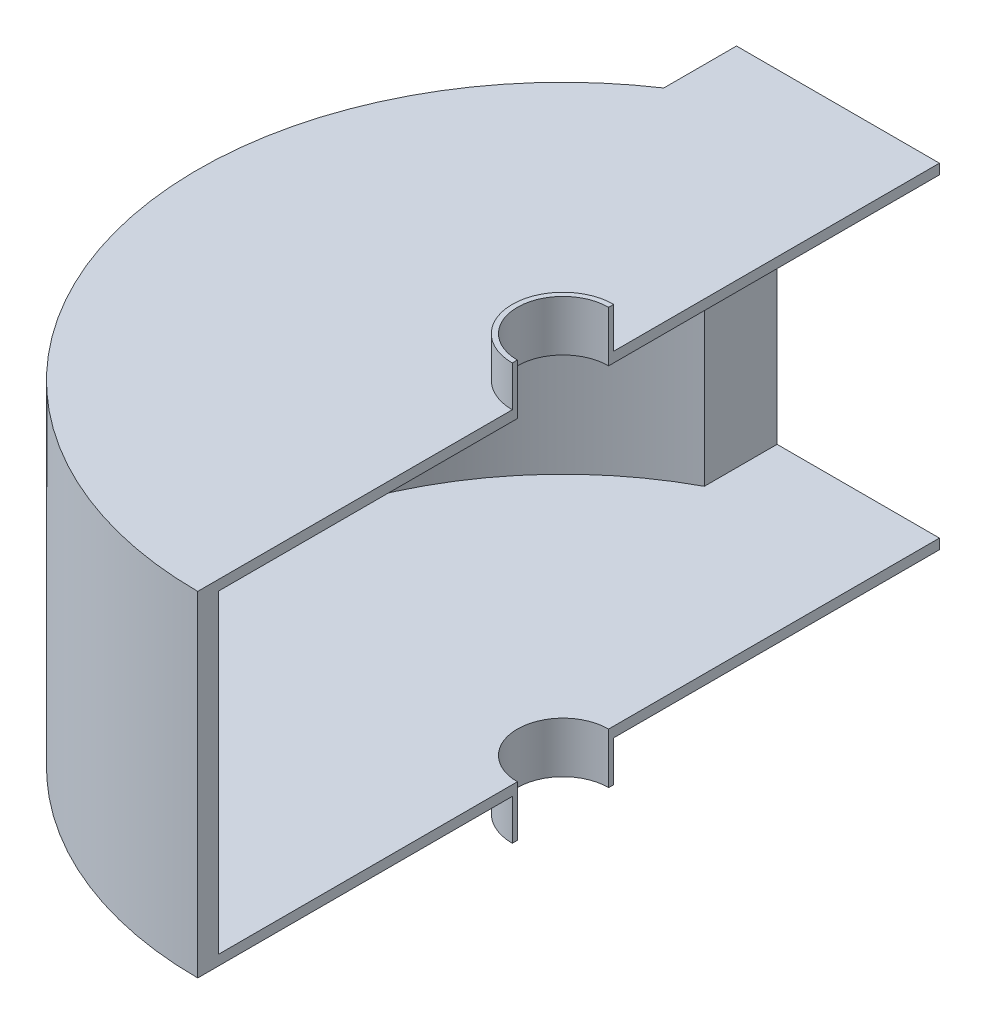
SolidWorks part; units mm, degrees
ref_plane "Front Plane" through (0, 0, 0) normal (0, 0, 1) x (1, 0, 0)
ref_plane "Top Plane" through (0, 0, 0) normal (0, 1, 0) x (1, 0, 0)
ref_plane "Right Plane" through (0, 0, 0) normal (1, 0, 0) x (0, 0, -1)
sketch "Sketch1" plane through (0, 0, 0) normal (0, 1, 0) x (1, 0, 0)
  line L0 (0, 25) -> (0, 22.5)
  line L1 (0, -22.5) -> (0, -25)
  arc A0 (0, 22.5) -> (0, -22.5) centre (0, 0) ccw
  arc A1 (0, 25) -> (0, -25) centre (0, 0) ccw
  dimension "D1" = 22.5
  dimension "D2" = 25
extrude "Boss-Extrude1" add sketch "Sketch1" along normal blind 20 and the other way blind 5
sketch "Sketch2" plane through (0, 0, 0) normal (0, 1, 0) x (1, 0, 0)
  line L0 (0, -25) -> (0, -180)
  line L1 (0, 25) -> (0, 185.5)
  line L2 (0, 185.5) -> (-100, 185.5)
  line L3 (-100, 185.5) -> (-100, 149.6663)
  arc A0 (-100, 149.6663) -> (0, -180) centre (0, 0) ccw
  arc A1 (0, -25) -> (0, 25) centre (0, 0) cw
  arc A2 (0, 25) -> (0, -25) centre (0, 0) ccw construction
  dimension "D1" = 360
  dimension "D2" = 185.5
  dimension "D3" = 100
extrude "Boss-Extrude2" add sketch "Sketch2" against normal blind 5 contours L0 A1 L1 L2 L3 A0
ref_plane "Plane1" through (0, -82.5, 0) normal (0, 1, 0) x (1, 0, 0)
mirror "Mirror1" about plane through (0, -82.5, 0) normal (0, 1, 0) of bodies 102
sketch "Sketch3" plane through (0, -5, 0) normal (0, -1, 0) x (1, 0, 0)
  line L0 (-100, -149.6663) -> (-100, -185.5)
  line L1 (-100, -185.5) -> (-80, -185.5)
  line L2 (0, -185.5) -> (-100, -185.5) construction
  line L3 (-80, -185.5) -> (-80, -149.6663)
  line L4 (0, 180) -> (0, 169.7056)
  arc A0 (0, 180) -> (-100, -149.6663) centre (0, 0) ccw
  arc A1 (0, 169.7056) -> (-80, -149.6663) centre (0, 0) ccw
  dimension "D1" = 20
extrude "Boss-Extrude3" add sketch "Sketch3" along normal up to next
